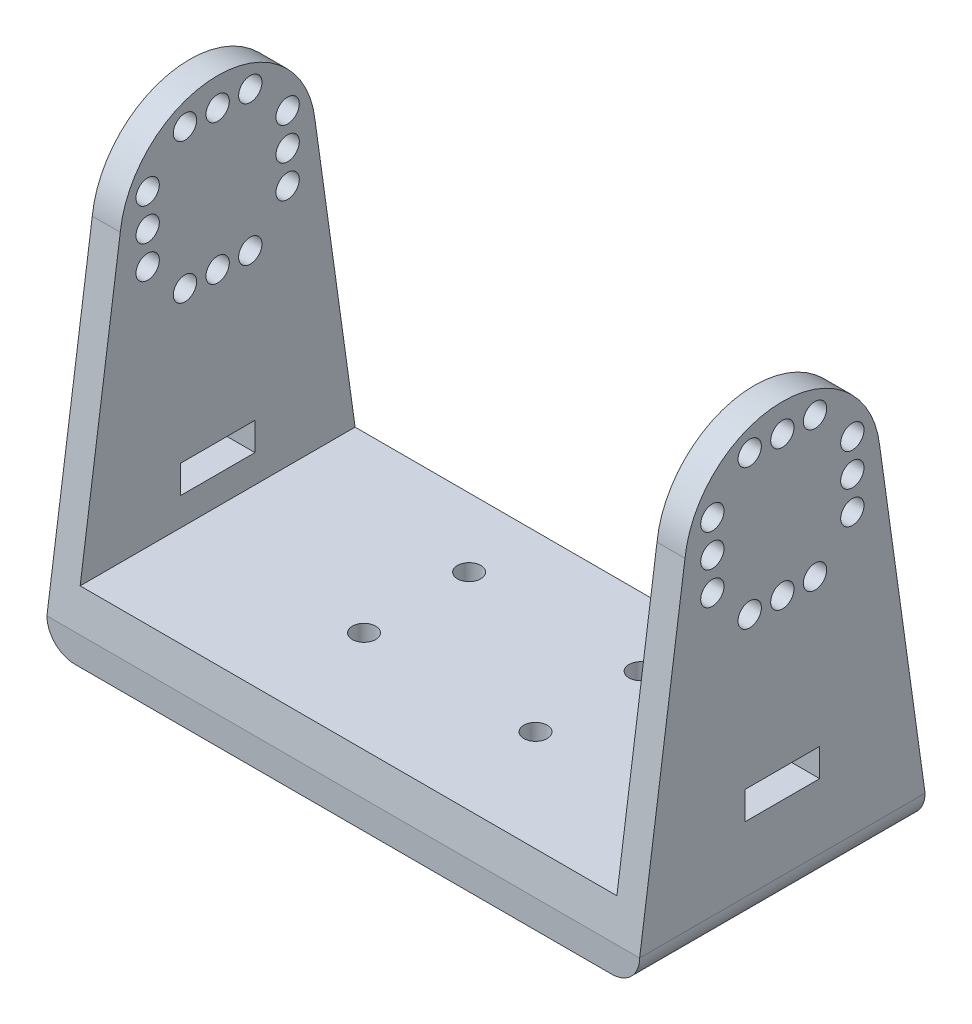
SolidWorks part; units mm, degrees
ref_plane "Front Plane" through (0, 0, 0) normal (0, 0, 1) x (1, 0, 0)
ref_plane "Top Plane" through (0, 0, 0) normal (0, 1, 0) x (1, 0, 0)
ref_plane "Right Plane" through (0, 0, 0) normal (1, 0, 0) x (0, 0, -1)
sketch "Sketch2" plane through (0, 0, 0) normal (0, 1, 0) x (1, 0, 0)
  line L1 (-52.0231, 30.2191) -> (11.4969, 30.2191)
  line L2 (-52.0231, 30.2191) -> (-52.0231, -0.3709)
  line L3 (-52.0231, -0.3709) -> (11.4969, -0.3709)
  line L4 (11.4969, 30.2191) -> (11.4969, -0.3709)
extrude "Boss-Extrude1" add sketch "Sketch2" along normal blind 7
sketch "Sketch3" plane through (0, 7, 0) normal (0, 1, 0) x (1, 0, 0)
  line L0 (-52.0231, 30.2191) -> (-49.0231, 30.2191)
  line L1 (11.4969, 30.2191) -> (-52.0231, 30.2191) construction
  line L2 (-49.0231, 30.2191) -> (-49.0231, -0.3709)
  line L3 (-52.0231, -0.3709) -> (11.4969, -0.3709) construction
  line L4 (-49.0231, -0.3709) -> (-52.0231, -0.3709)
  line L5 (-52.0231, -0.3709) -> (-52.0231, 30.2191)
  line L6 (11.4969, 30.2191) -> (8.4969, 30.2191) construction
  line L7 (8.4969, 30.2191) -> (8.4969, -0.3709) construction
  line L8 (8.4969, -0.3709) -> (11.4969, -0.3709) construction
  line L9 (11.4969, -0.3709) -> (11.4969, 30.2191) construction
  line L10 (11.4969, -0.3709) -> (11.4969, 30.2191) construction
  line L11 (8.4969, 30.2191) -> (11.4969, 30.2191)
  line L12 (11.4969, 30.2191) -> (11.4969, -0.3709)
  line L13 (11.4969, -0.3709) -> (8.4969, -0.3709)
  line L14 (8.4969, -0.3709) -> (8.4969, 30.2191)
extrude "Boss-Extrude2" add sketch "Sketch3" along normal blind 40
fillet "Fillet2" radius 3 2 edges at (11.4969, 0, -14.9241) (-52.0231, 0, -14.9241)
sketch "Sketch4" plane through (-52.0231, 0, 0) normal (-1, 0, 0) x (0, 0, 1)
  line L0 (-30.2191, 3) -> (-30.2191, 47) construction
  line L1 (-30.2191, 47) -> (-30.2191, 25) construction
  line L2 (-30.2191, 25) -> (-30.2191, 36) construction
  line L3 (-14.9241, 3) -> (-14.9241, 47) construction
  line L4 (-30.2191, 47) -> (0.3709, 47) construction
  line L5 (-14.9241, 47) -> (-14.9241, 26) construction
  line L6 (-14.9241, 36.5) -> (-7.4241, 36.5) construction
  line L7 (-7.4241, 36.5) -> (-7.4241, 40) construction
  line L8 (-7.4241, 36.5) -> (-7.4241, 33) construction
  line L9 (-14.9241, 36.5) -> (-14.9241, 29) construction
  line L10 (-14.9241, 29) -> (-11.4241, 29) construction
  line L11 (-14.9241, 29) -> (-18.4241, 29) construction
  line L12 (-14.9241, 36.5) -> (-22.4241, 36.5) construction
  line L13 (-22.4241, 36.5) -> (-22.4241, 40) construction
  line L14 (-22.4241, 36.5) -> (-22.4241, 33) construction
  line L15 (-14.9241, 36.5) -> (-14.9241, 44) construction
  line L16 (-14.9241, 44) -> (-11.4241, 44) construction
  line L17 (-11.4241, 44) -> (-18.4241, 44) construction
  line L18 (-22.4241, 38.25) -> (-25.2772, 38.25) construction
  line L19 (0.3709, 3) -> (-30.2191, 3) construction
  line L20 (-25.2772, 38.25) -> (-4.571, 38.25) construction
  line L21 (-25.2772, 38.25) -> (-30.2191, 3)
  line L22 (-30.2191, 3) -> (0.3709, 3)
  line L23 (0.3709, 3) -> (-4.571, 38.25)
  circle A0 centre (-14.9241, 36.5) radius 10.5
  circle A1 centre (-7.4241, 36.5) radius 1.25
  circle A2 centre (-7.4241, 40) radius 1.25
  circle A3 centre (-7.4241, 33) radius 1.25
  circle A4 centre (-14.9241, 29) radius 1.25
  circle A5 centre (-11.4241, 29) radius 1.25
  circle A6 centre (-18.4241, 29) radius 1.25
  circle A7 centre (-22.4241, 36.5) radius 1.25
  circle A8 centre (-22.4241, 40) radius 1.25
  circle A9 centre (-22.4241, 33) radius 1.25
  circle A10 centre (-11.4241, 44) radius 1.25
  circle A11 centre (-18.4241, 44) radius 1.25
  circle A12 centre (-14.9241, 44) radius 1.25
extrude "Cut-Extrude2" cut sketch "Sketch4" against normal blind 70
sketch "Sketch7" plane through (0, 7, 0) normal (0, 1, 0) x (1, 0, 0)
  line L0 (8.9219, 28.867) -> (8.9219, -0.0188) construction
  line L1 (8.9219, -0.0188) -> (-49.4481, -0.0188) construction
  line L2 (-49.4481, -0.0188) -> (-49.4481, 28.867) construction
  line L3 (-49.4481, 28.867) -> (8.9219, 28.867) construction
  line L4 (8.9219, 28.867) -> (-20.2631, 28.867) construction
  line L8 (-29.4541, 11.0415) -> (-11.0731, 11.0415) construction
  line L9 (-29.4541, 22.305) -> (-11.0731, 22.305) construction
  circle A0 centre (-11.0731, 11.0415) radius 1.25
  circle A1 centre (-11.0731, 22.305) radius 1.25
  circle A2 centre (-29.4541, 11.0415) radius 1.25
  circle A3 centre (-29.4541, 22.305) radius 1.25
extrude "Cut-Extrude4" cut sketch "Sketch7" against normal blind 20 and the other way blind 6
sketch "Sketch11" plane through (-52.0231, 0, 0) normal (-1, 0, 0) x (0, 0, 1)
  line L0 (-14.9241, 3) -> (-14.9241, 13) construction
  line L1 (-30.2191, 3) -> (0.3709, 3) construction
  line L2 (-14.9241, 13) -> (-18.9241, 13)
  line L3 (-18.9241, 13) -> (-10.9241, 13)
  line L4 (-10.9241, 13) -> (-10.9241, 10)
  line L5 (-10.9241, 10) -> (-18.9241, 10)
  line L6 (-18.9241, 10) -> (-18.9241, 13)
extrude "Cut-Extrude5" cut sketch "Sketch11" against normal blind 80 contours L5 L0 L2 L6 | L0 L5 L4 L3
